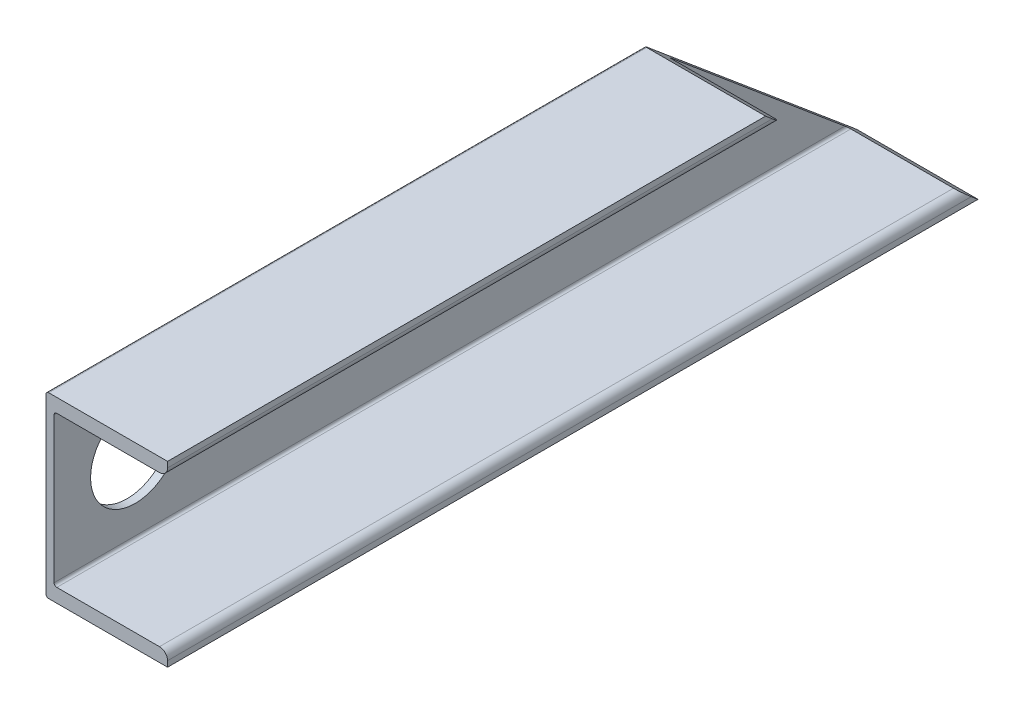
SolidWorks part; units mm, degrees
material "Gray Cast Iron"
ref_plane "Front Plane" through (0, 0, 0) normal (0, 0, 1) x (1, 0, 0)
ref_plane "Top Plane" through (0, 0, 0) normal (0, 1, 0) x (1, 0, 0)
ref_plane "Right Plane" through (0, 0, 0) normal (1, 0, 0) x (0, 0, -1)
sketch "Sketch1" plane through (0, 0, 0) normal (0, 0, 1) x (1, 0, 0)
  line L0 (0, 33) -> (0, -33)
  line L1 (0, -33) -> (45, -33)
  line L2 (0, 33) -> (45, 33)
  line L3 (45, -33) -> (45, -27.9)
  line L4 (45, -27.9) -> (3, -27.9)
  line L5 (3, -27.9) -> (3, 27.9)
  line L6 (3, 27.9) -> (45, 27.9)
  line L7 (45, 27.9) -> (45, 33)
  point P4 (0, 0)
  dimension "D1" = 66
  dimension "D2" = 45
  dimension "D3" = 45
  dimension "D4" = 5.1
  dimension "D5" = 5.1
  dimension "D6" = 42
extrude "Boss-Extrude1" add sketch "Sketch1" along normal blind 300
sketch "Sketch3" plane through (0, 0, 0) normal (-1, 0, 0) x (0, 0, 1)
  line L1 (300, 33) -> (0, 33) construction
  line L4 (0, -33) -> (0, 33)
  line L5 (0, 33) -> (0, -33) construction
  line L6 (0, 33) -> (78.6557, 33)
  line L7 (78.6557, 33) -> (0, -33)
  dimension "D2" = 50
extrude "Cut-Extrude1" cut sketch "Sketch3" against normal up to next
fillet "Fillet1" radius 3 2 edges at (45, -27.9, 153.039) (45, 27.9, 186.2889)
fillet "Fillet2" radius 1 4 edges at (3, -27.9, 153.039) (0, -33, 150) (0, 33, 189.3279) (3, 27.9, 186.2889)
sketch "Sketch4" plane through (0, 0, 0) normal (-1, 0, 0) x (0, 0, 1)
  line L0 (300, 0) -> (39.3279, 0) construction
  line L1 (300, 32) -> (300, -32) construction
  line L2 (1.1918, -32) -> (77.464, 32) construction
  circle A0 centre (270, 0) radius 16.5
  dimension "D1" = 33
  dimension "D2" = 30
extrude "Cut-Extrude2" cut sketch "Sketch4" against normal blind 10
